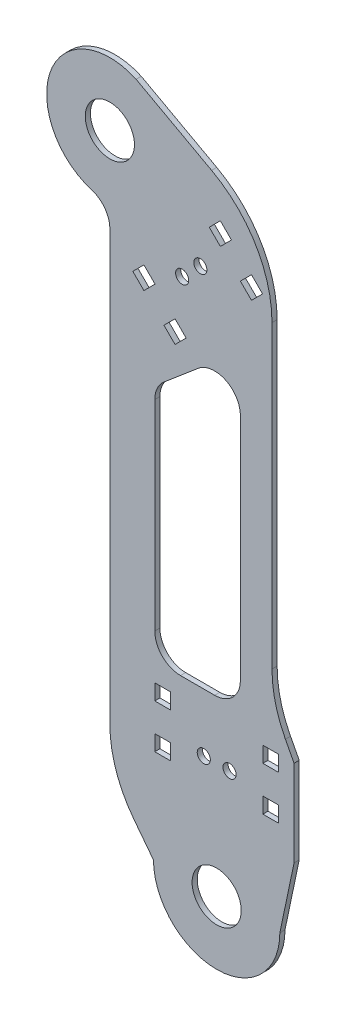
SolidWorks part; units mm, degrees
ref_plane "前视基准面" through (0, 0, 0) normal (0, 0, 1) x (1, 0, 0)
ref_plane "上视基准面" through (0, 0, 0) normal (0, 1, 0) x (1, 0, 0)
ref_plane "右视基准面" through (0, 0, 0) normal (1, 0, 0) x (0, 0, -1)
sketch "草图1" plane through (0, 0, 0) normal (0, 0, 1) x (1, 0, 0)
  line L0 (-10.1959, 211.8389) -> (-55.1959, 211.8389) construction
  line L1 (-10.1959, 211.8389) -> (21.6239, 180.0191) construction
  line L4 (17.8913, 176.6806) -> (24.9624, 183.7517) construction
  line L6 (26.7655, 181.9485) -> (19.6944, 174.8775) construction
  line L8 (23.9371, 177.7059) -> (9.0878, 162.8567) construction
  line L10 (21.6239, 180.0191) -> (23.9371, 177.7059) construction
  line L12 (23.9371, 177.7059) -> (29.9828, 171.6601) construction
  line L18 (29.9828, 171.6601) -> (15.1336, 156.8109) construction
  line L20 (15.1336, 156.8109) -> (9.0878, 162.8567) construction
  line L21 (15.1336, 152.4975) -> (19.447, 156.8109)
  line L22 (15.1336, 152.4975) -> (10.8203, 156.8109)
  line L23 (19.447, 156.8109) -> (15.1336, 161.1242)
  line L24 (10.8203, 156.8109) -> (15.1336, 161.1242)
  line L25 (15.1336, 152.4975) -> (15.1336, 161.1242) construction
  line L26 (19.447, 156.8109) -> (10.8203, 156.8109) construction
  line L27 (3.0421, 164.5891) -> (7.3554, 168.9024)
  line L28 (3.0421, 173.2158) -> (7.3554, 168.9024)
  line L29 (-1.2713, 168.9024) -> (3.0421, 173.2158)
  line L30 (-1.2713, 168.9024) -> (3.0421, 164.5891)
  line L31 (44.8321, 182.196) -> (40.5187, 186.5094)
  line L32 (49.1454, 186.5094) -> (44.8321, 190.8227)
  line L33 (49.1454, 186.5094) -> (44.8321, 182.196)
  line L34 (44.8321, 190.8227) -> (40.5187, 186.5094)
  line L35 (37.0539, 198.6009) -> (32.7406, 194.2875)
  line L36 (32.7406, 202.9143) -> (28.4272, 198.6009)
  line L37 (28.4272, 198.6009) -> (32.7406, 194.2875)
  line L38 (32.7406, 202.9143) -> (37.0539, 198.6009)
  line L39 (18.0883, 240.1232) -> (52.8041, 205.4074) construction
  line L49 (52.8041, 93.3389) -> (-10.1959, 93.3389) construction
  line L50 (-29.6695, 176.8992) -> (-10.1959, 166.0457) construction
  line L53 (-10.1959, 93.3389) -> (-10.1959, 166.0457)
  line L54 (52.8041, 93.3389) -> (52.8041, 205.4074)
  line L58 (21.3041, 93.3389) -> (21.3041, -25.1611) construction
  line L96 (7.2541, 34.7103) -> (13.3541, 34.7103)
  line L97 (7.2541, 34.7103) -> (7.2541, 28.6103)
  line L98 (7.2541, 28.6103) -> (13.3541, 28.6103)
  line L99 (13.3541, 34.7103) -> (13.3541, 28.6103)
  line L100 (7.2541, 34.7103) -> (13.3541, 28.6103) construction
  line L101 (7.2541, 28.6103) -> (13.3541, 34.7103) construction
  line L102 (7.2541, 17.6103) -> (13.3541, 17.6103)
  line L103 (7.2541, 11.5103) -> (7.2541, 17.6103)
  line L104 (7.2541, 11.5103) -> (13.3541, 11.5103)
  line L105 (13.3541, 11.5103) -> (13.3541, 17.6103)
  line L116 (52.8041, 93.3389) -> (52.8041, 8.5694) construction
  line L117 (31.3041, -25.1611) -> (31.3041, 2.2062) construction
  line L118 (49.2541, 11.5103) -> (49.2541, 17.6103)
  line L119 (55.3541, 11.5103) -> (49.2541, 11.5103)
  line L120 (55.3541, 11.5103) -> (55.3541, 17.6103)
  line L121 (55.3541, 17.6103) -> (49.2541, 17.6103)
  line L122 (55.3541, 28.6103) -> (49.2541, 34.7103) construction
  line L123 (55.3541, 34.7103) -> (49.2541, 28.6103) construction
  line L124 (49.2541, 34.7103) -> (49.2541, 28.6103)
  line L125 (55.3541, 28.6103) -> (49.2541, 28.6103)
  line L126 (55.3541, 34.7103) -> (55.3541, 28.6103)
  line L127 (55.3541, 34.7103) -> (49.2541, 34.7103)
  line L128 (52.8041, 93.3389) -> (52.8041, 50.9542)
  line L129 (52.8041, 50.9542) -> (61.3871, 34.7103)
  line L130 (61.3871, 34.7103) -> (61.3871, 1.202)
  line L131 (-10.1959, 93.3389) -> (-10.1959, -3.1129)
  line L132 (-10.1959, -3.1129) -> (-8.6959, -25.1611) construction
  line L133 (61.3871, 1.202) -> (55.8541, -25.1611)
  line L134 (-10.1959, -3.1129) -> (6.7541, -25.1611)
  line L135 (-10.1959, 166.0457) -> (-10.1959, 187.2889)
  line L136 (52.8041, 205.4074) -> (0, 234.1715)
  line L140 (7.2541, 42.1432) -> (7.2541, 134.6688)
  line L141 (7.2541, 134.6688) -> (40.5187, 162.8567)
  line L142 (40.5187, 162.8567) -> (40.5187, 42.1432)
  line L143 (40.5187, 42.1432) -> (7.2541, 42.1432)
  circle A0 centre (-10.1959, 211.8389) radius 9.55
  circle A1 centre (-10.1959, 211.8389) radius 40 construction
  circle A6 centre (-10.1959, 211.8389) radius 20.528 construction
  circle A8 centre (-10.1959, 211.8389) radius 45 construction
  circle A9 centre (24.9624, 183.7517) radius 2.55
  circle A10 centre (17.8913, 176.6806) radius 2.55
  arc A13 (18.0883, 240.1232) -> (-29.6695, 176.8992) centre (-10.1959, 211.8389) ccw construction
  circle A21 centre (21.3041, -25.1611) radius 40 construction
  circle A25 centre (26.3041, 19.5603) radius 2.55
  circle A26 centre (21.3041, -25.1611) radius 5.05 construction
  circle A27 centre (31.3041, -25.1611) radius 9.55
  circle A28 centre (31.3041, -25.1611) radius 40 construction
  circle A30 centre (36.3041, 19.5603) radius 2.55
  arc A31 (-8.6959, -25.1611) -> (61.3871, 1.202) centre (31.3041, -25.1611) ccw construction
  circle A32 centre (31.3041, -25.1611) radius 24.55 construction
  arc A33 (6.7541, -25.1611) -> (55.8541, -25.1611) centre (31.3041, -25.1611) ccw
  circle A34 centre (-10.1959, 211.8389) radius 24.55 construction
  arc A35 (0, 234.1715) -> (-10.1959, 187.2889) centre (-10.1959, 211.8389) ccw
  dimension "D10" = 19.1
  dimension "D13" = 80
  dimension "D14" = 118.5
  dimension "D5" = 1
  dimension "D6" = 90
  dimension "D3" = 5.1
  dimension "D12" = 80
  dimension "D16" = 15
  dimension "D17" = 5.1
  dimension "D18" = 15
  dimension "D25" = 10
  dimension "D26" = 19.1
  dimension "D2" = 135
  dimension "D4" = 10
  dimension "D7" = 21
  dimension "D8" = 8.55
  dimension "D9" = 6.1
  dimension "D11" = 6.1
  dimension "D15" = 118.5
  dimension "D23" = 6.1
  dimension "D24" = 6.1
extrude "凸台-拉伸2" add sketch "草图1" along normal blind 2
fillet "圆角1" radius 45 3 edges at (52.8041, 50.9542, 1) (-10.1959, -3.1129, 1) (52.8041, 205.4074, 1)
fillet "圆角2" radius 10 5 edges at (-10.1959, 187.2889, 1) (40.5187, 42.1432, 1) (7.2541, 42.1432, 1) (7.2541, 134.6688, 1) (40.5187, 162.8567, 1)
